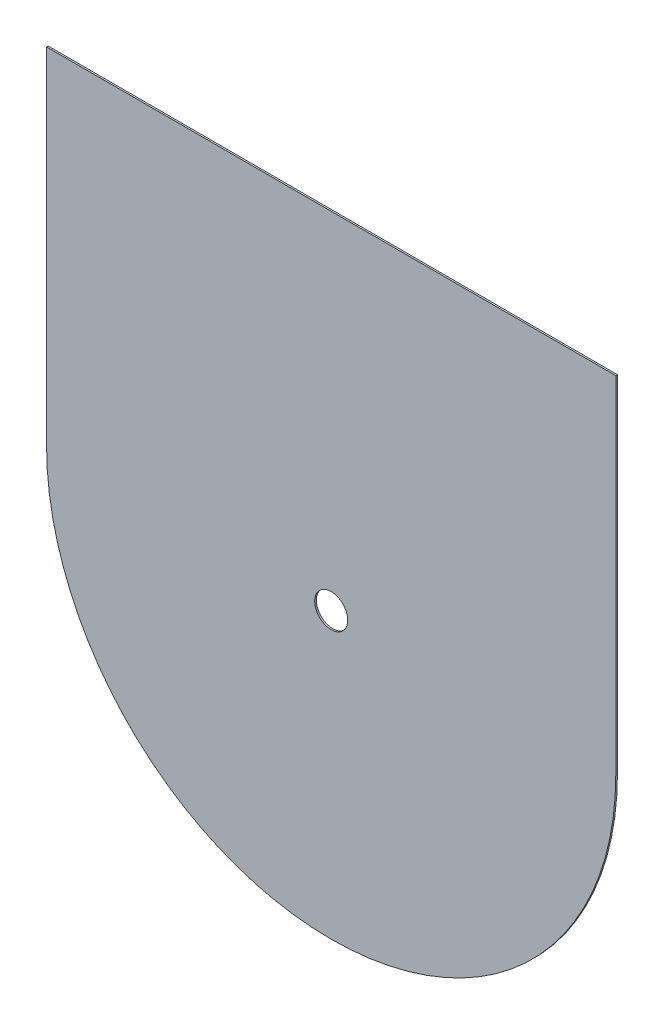
SolidWorks part; units mm, degrees
ref_plane "Front Plane" through (0, 0, 0) normal (0, 0, 1) x (1, 0, 0)
ref_plane "Top Plane" through (0, 0, 0) normal (0, 1, 0) x (1, 0, 0)
ref_plane "Right Plane" through (0, 0, 0) normal (1, 0, 0) x (0, 0, -1)
sketch "Sketch1" plane through (0, 0, 0) normal (0, 0, 1) x (1, 0, 0)
  line L0 (-375.9021, -7.0612) -> (-375.9021, 412.0388)
  line L1 (-373.9021, -7.0612) -> (-373.9021, 412.0388)
  line L2 (-373.9021, 412.0388) -> (311.8979, 412.0388)
  line L3 (311.8979, -7.0612) -> (311.8979, 412.0388)
  line L4 (313.8979, -7.0612) -> (313.8979, 412.0388)
  line L5 (-373.9021, 412.0388) -> (-375.9021, 412.0388)
  line L6 (311.8979, 412.0388) -> (313.8979, 412.0388)
  arc A0 (-373.9021, -7.0612) -> (311.8979, -7.0612) centre (-31.0021, -7.0612) ccw
  arc A1 (-375.9021, -7.0612) -> (313.8979, -7.0612) centre (-31.0021, -7.0612) ccw
  circle A2 centre (-31.0021, -7.0612) radius 20
  dimension "D1" = 685.8
  dimension "D2" = 40
extrude "Boss-Extrude1" add sketch "Sketch1" along normal blind 2 contours L1 A0 L3 L2 | L0 A1 L4 L6 L3 A0 L1 L5
